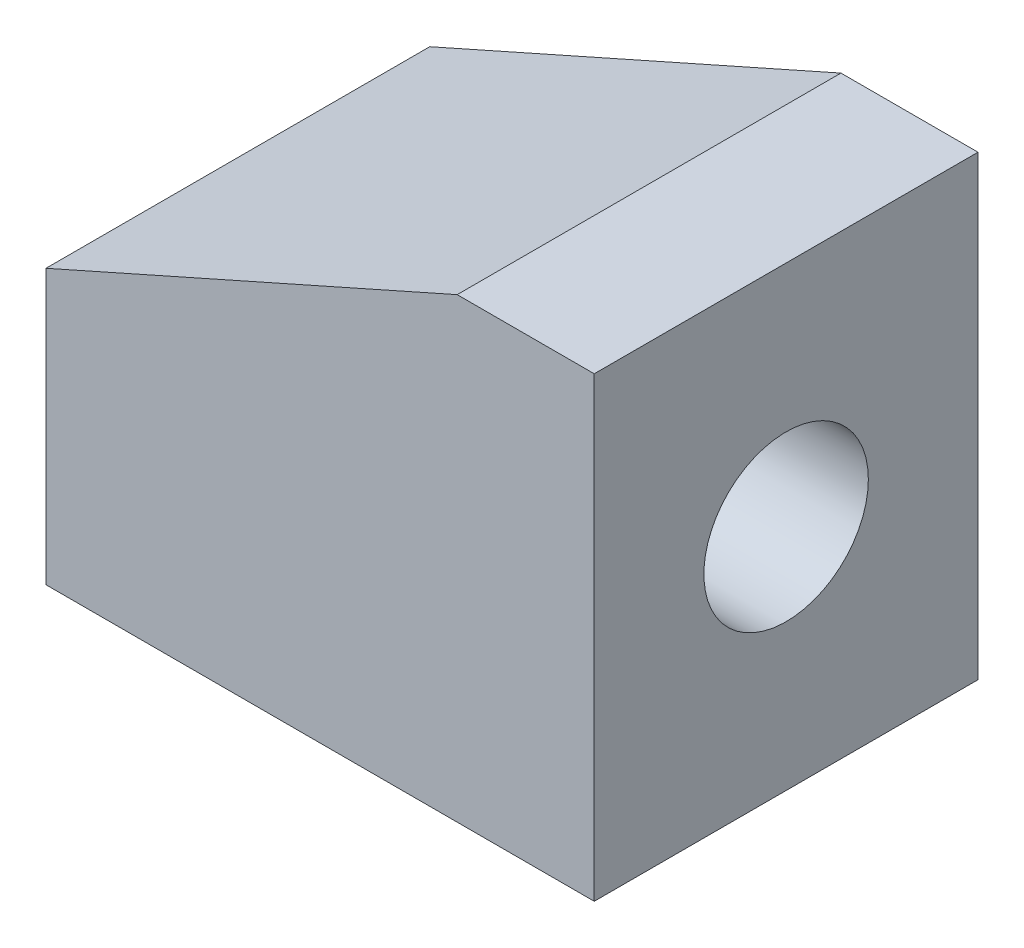
SolidWorks part; units mm, degrees
ref_plane "Front Plane" through (0, 0, 0) normal (0, 0, 1) x (1, 0, 0)
ref_plane "Top Plane" through (0, 0, 0) normal (0, 1, 0) x (1, 0, 0)
ref_plane "Right Plane" through (0, 0, 0) normal (1, 0, 0) x (0, 0, -1)
sketch "Sketch1" plane through (0, 0, 0) normal (0, 0, 1) x (1, 0, 0)
  line L0 (-30, 0) -> (30, 0)
  line L1 (30, 0) -> (30, 50)
  line L2 (30, 50) -> (15, 50)
  line L3 (15, 50) -> (-30, 30)
  line L4 (-30, 30) -> (-30, 0)
  dimension "D1" = 15
  dimension "D2" = 50
  dimension "D3" = 30
  dimension "D4" = 60
  dimension "D5" = 30
extrude "Boss-Extrude1" add sketch "Sketch1" against normal blind 42
sketch "Sketch2" plane through (30, 0, 0) normal (1, 0, 0) x (0, 0, -1)
  line L0 (0, 0) -> (0, 50) construction
  line L2 (42, 0) -> (0, 0) construction
  circle A0 centre (21, 25) radius 9
  dimension "D1" = 18
  dimension "D2" = 21
  dimension "D3" = 25
extrude "Cut-Extrude1" cut sketch "Sketch2" against normal blind 40
